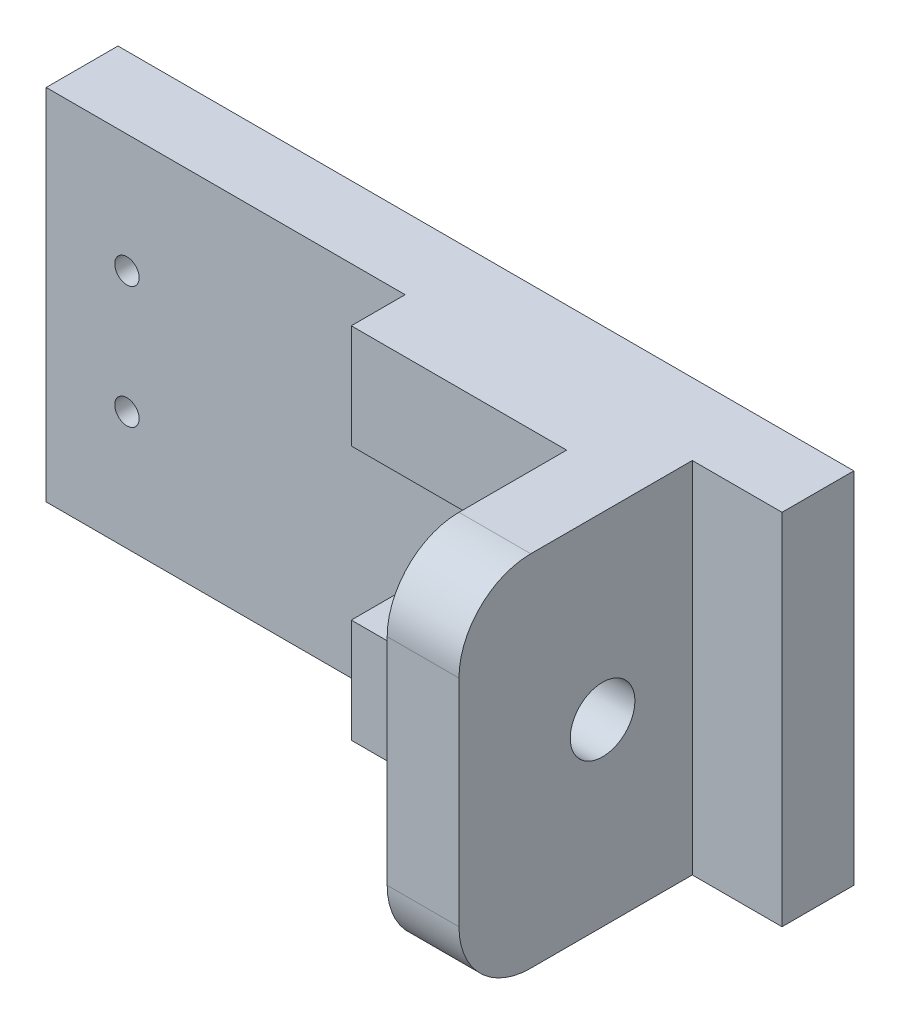
SolidWorks part; units mm, degrees
ref_plane "Piano frontale" through (0, 0, 0) normal (0, 0, 1) x (1, 0, 0)
ref_plane "Piano superiore" through (0, 0, 0) normal (0, 1, 0) x (1, 0, 0)
ref_plane "Piano destro" through (0, 0, 0) normal (1, 0, 0) x (0, 0, -1)
sketch "Schizzo1" plane through (0, 0, 0) normal (0, 0, 1) x (1, 0, 0)
  line L1 (102.5, -50) -> (-102.5, -50)
  line L2 (102.5, -50) -> (102.5, 50)
  line L3 (102.5, 50) -> (-102.5, 50)
  line L4 (-102.5, -50) -> (-102.5, 50)
  line L5 (102.5, -50) -> (-102.5, 50) construction
  line L6 (102.5, 50) -> (-102.5, -50) construction
  point P0 (0, 0)
  dimension "D1" = 205
  dimension "D2" = 100
extrude "Estrusione-Estrusione1" add sketch "Schizzo1" along normal blind 20
sketch "Schizzo2" plane through (0, 0, 20) normal (0, 0, 1) x (1, 0, 0)
  line L0 (102.5, 50) -> (-102.5, 50) construction
  line L1 (77.5, -50) -> (57.5, -50)
  line L2 (77.5, -50) -> (77.5, 50)
  line L3 (77.5, 50) -> (57.5, 50)
  line L4 (57.5, -50) -> (57.5, 50)
  line L5 (77.5, -50) -> (57.5, 50) construction
  line L6 (77.5, 50) -> (57.5, -50) construction
  line L7 (-102.5, -50) -> (102.5, -50) construction
  line L8 (102.5, -50) -> (102.5, 50) construction
  point P0 (67.5, 0)
  dimension "D1" = 25
  dimension "D2" = 20
extrude "Estrusione-Estrusione2" add sketch "Schizzo2" along normal blind 65
sketch "Schizzo3" plane through (57.5, 0, 0) normal (-1, 0, 0) x (0, 0, 1)
  line L0 (85, 50) -> (85, -50) construction
  line L1 (85, 50) -> (20, 50) construction
  line L2 (85, -50) -> (20, -50) construction
  line L3 (65, 50) -> (85, 50)
  line L4 (85, 50) -> (85, 30)
  line L5 (85, -30) -> (85, -50)
  line L6 (85, -50) -> (65, -50)
  arc A0 (85, 30) -> (65, 50) centre (65, 30) ccw
  arc A1 (65, -50) -> (85, -30) centre (65, -30) ccw
  dimension "D1" = 40
extrude "Taglio-Estrusione1" cut sketch "Schizzo3" against normal blind 20
sketch "Schizzo4" plane through (57.5, 0, 0) normal (-1, 0, 0) x (0, 0, 1)
  line L0 (20, 50) -> (20, -50) construction
  circle A0 centre (45, 0) radius 9
  dimension "D1" = 18
  dimension "D2" = 25
extrude "Taglio-Estrusione2" cut sketch "Schizzo4" against normal blind 20
sketch "Schizzo5" plane through (0, 0, 20) normal (0, 0, 1) x (1, 0, 0)
  line L1 (57.5, -50) -> (-2.5, -50)
  line L2 (57.5, -50) -> (57.5, -21)
  line L3 (57.5, -21) -> (-2.5, -21)
  line L4 (-2.5, -50) -> (-2.5, -21)
  line L5 (57.5, 50) -> (-2.5, 50)
  line L6 (57.5, 50) -> (57.5, 21)
  line L7 (57.5, 21) -> (-2.5, 21)
  line L8 (-2.5, 50) -> (-2.5, 21)
  dimension "D1" = 29
  dimension "D2" = 29
  dimension "D3" = 60
  dimension "D4" = 60
extrude "Estrusione-Estrusione3" add sketch "Schizzo5" along normal blind 15
sketch "Schizzo6" plane through (0, 0, 20) normal (0, 0, 1) x (1, 0, 0)
  line L0 (-102.5, 50) -> (-102.5, -50) construction
  line L1 (-102.5, -50) -> (-2.5, -50) construction
  circle A0 centre (-80, 17) radius 4
  circle A1 centre (-80, -17) radius 4
  dimension "D1" = 8
  dimension "D2" = 22.5
  dimension "D3" = 22.5
  dimension "D4" = 33
  dimension "D5" = 34
hole_wizard "Foro filettato M8-1" positions "Schizzo3D1" profile "Schizzo7" tap size "M8" standard "ISO" end condition through all
sketch3d "Schizzo3D1"
  point P0 (-80, 17, 20)
  point P3 (-80, -17, 20)
cosmetic thread "Filettatura del foro1" parameters "D2"=8
cosmetic thread "Filettatura del foro2" parameters "D2"=8
sketch "Schizzo7" plane through (-80, 17, 20) normal (1, 0, 0) x (0, -1, 0)
  line L0 (0, 0) -> (0, 20)
  line L1 (0, 20) -> (3.4, 20)
  line L2 (3.4, 20) -> (3.4, 0)
  line L5 (3.4, 0) -> (0, 0)
  line L11 (0, -6.35) -> (0, 107.95) construction
  dimension "Thru Tap Drill Dia." = 6.8
  dimension "Thru Tap Drill Depth" = 20
